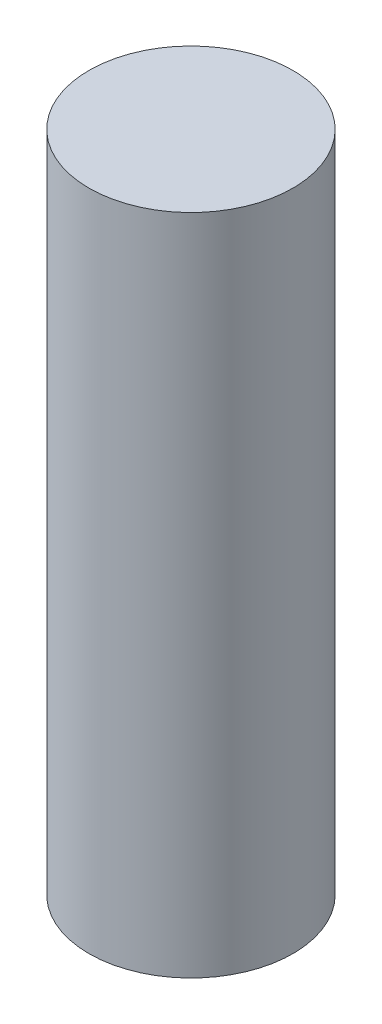
SolidWorks part; units mm, degrees
ref_plane "X-Y Datum" through (0, 0, 0) normal (0, 0, 1) x (1, 0, 0)
ref_plane "X-Z Datum" through (0, 0, 0) normal (0, 1, 0) x (1, 0, 0)
ref_plane "Y-Z Datum" through (0, 0, 0) normal (1, 0, 0) x (0, 0, -1)
sketch "Sketch1" plane through (0, 0, 0) normal (0, 1, 0) x (1, 0, 0)
  circle A0 centre (0, 0) radius 5.08
extrude "Boss-Extrude1" add sketch "Sketch1" along normal blind 33.02 contours A0
